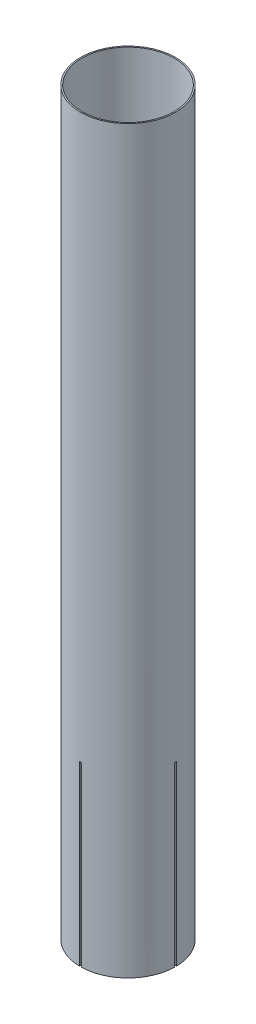
SolidWorks part; units mm, degrees
ref_plane "Front Plane" through (0, 0, 0) normal (0, 0, 1) x (1, 0, 0)
ref_plane "Top Plane" through (0, 0, 0) normal (0, 1, 0) x (1, 0, 0)
ref_plane "Right Plane" through (0, 0, 0) normal (1, 0, 0) x (0, 0, -1)
sketch "Sketch1" plane through (0, 0, 0) normal (0, 1, 0) x (1, 0, 0)
  circle A0 centre (0, 0) radius 76.2
  circle A1 centre (0, 0) radius 78.359
  dimension "D1" = 156.718
  dimension "D2" = 152.4
extrude "Boss-Extrude1" add sketch "Sketch1" along normal blind 1219.2
sketch "Sketch2" plane through (0, 0, 0) normal (0, 0, 1) x (1, 0, 0)
  line L0 (0, 0) -> (0, 1219.2) construction
  line L1 (76.2, 1219.2) -> (-76.2, 1219.2) construction
  line L3 (-1.5875, 292.1) -> (1.5875, 292.1)
  line L4 (-1.5875, 292.1) -> (-1.5875, 0)
  line L5 (-1.5875, 0) -> (1.5875, 0)
  line L6 (1.5875, 292.1) -> (1.5875, 0)
  line L7 (-1.5875, 292.1) -> (1.5875, 0) construction
  line L8 (-1.5875, 0) -> (1.5875, 292.1) construction
  point P5 (0, 146.05)
  dimension "D1" = 3.175
  dimension "D2" = 292.1
extrude "Cut-Extrude2" cut sketch "Sketch2" along normal through all
pattern_circular "CirPattern1" count 4 over 360 about axis through (0, 0, 0) along (0, 1, 0) of "Cut-Extrude2"
